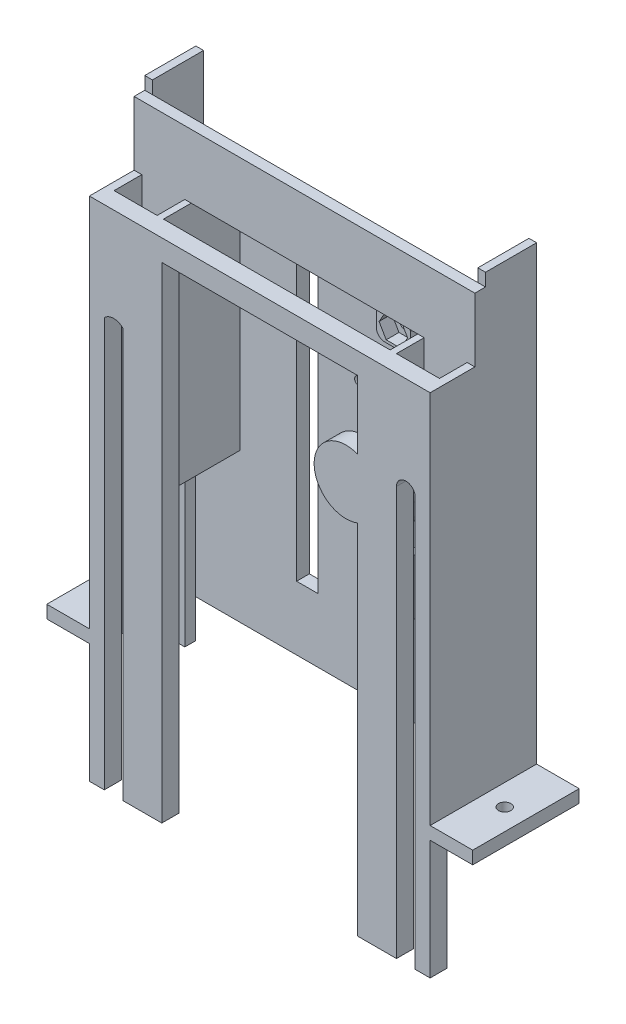
SolidWorks part; units mm, degrees
ref_plane "Front Plane" through (0, 0, 0) normal (0, 0, 1) x (1, 0, 0)
ref_plane "Top Plane" through (0, 0, 0) normal (0, 1, 0) x (1, 0, 0)
ref_plane "Right Plane" through (0, 0, 0) normal (1, 0, 0) x (0, 0, -1)
sketch "Sketch1" plane through (0, 0, 0) normal (0, 0, 1) x (1, 0, 0)
  line L0 (0, 87.3129) -> (0, -99.6485)
  line L1 (-40, 28) -> (40, 28)
  line L2 (-40, 28) -> (-40, -28)
  line L3 (-40, -28) -> (40, -28)
  line L4 (40, 28) -> (40, -28)
  line L5 (-40, 28) -> (40, -28) construction
  line L6 (-40, -28) -> (40, 28) construction
  line L7 (-23, 58.4535) -> (-23, -153.9501)
  line L8 (-36.5, -28) -> (-36.5, 23)
  line L13 (-36.5, 23) -> (-32.1, 23)
  line L14 (-32.1, 23) -> (-32.1, -28)
  line L15 (23, 58.4535) -> (23, -153.9501)
  line L16 (32.1, 23) -> (32.1, -28)
  line L17 (36.5, 23) -> (32.1, 23)
  line L18 (36.5, -28) -> (36.5, 23)
  line L19 (40, 28) -> (40, -28)
  line L20 (-34.3, 23) -> (34.3, 23)
  arc A0 (-36.5, 23) -> (-32.1, 23) centre (-34.3, 23) cw
  arc A1 (36.5, 23) -> (32.1, 23) centre (34.3, 23) ccw
  point P0 (0, 0)
  dimension "D1" = 17
  dimension "D2" = 80
  dimension "D3" = 56
  dimension "D4" = 4.4
  dimension "D5" = 5
  dimension "D6" = 3.5
extrude "Boss-Extrude1" add sketch "Sketch1" along normal blind 4 contours L8 A0 L20 L7 L1 L2 L3 | L20 L14 L3 L7 | L7 L20 L0 L1 | L20 L15 L3 L16 | L0 L20 L15 L1 | A1 L18 L3 L4 L1 L15 L20
sketch "Sketch2" plane through (0, 0, 0) normal (0, 0, -1) x (-1, 0, 0)
  line L0 (-38.2, 28) -> (-38.2, -28)
  line L1 (-28.1, 28) -> (-28.1, -28)
  line L2 (-26.6, 28) -> (-26.6, -28)
  line L3 (0, 45.2622) -> (0, -39.8517) construction
  line L4 (36.5, -28) -> (36.5, 23)
  line L5 (40, -28) -> (36.5, -28)
  line L6 (40, 28) -> (40, -28)
  line L7 (23, -28) -> (23, 23)
  line L8 (32.1, -28) -> (23, -28)
  line L9 (32.1, 23) -> (32.1, -28)
  line L10 (26.6, 28) -> (26.6, -28)
  line L11 (28.1, 28) -> (28.1, -28)
  line L12 (38.2, 28) -> (38.2, -28)
  line L14 (-32.1, 23) -> (-32.1, -28)
  line L15 (-32.1, -28) -> (-23, -28)
  line L16 (-23, -28) -> (-23, 23)
  line L17 (-23, 23) -> (23, 23)
  line L18 (23, 23) -> (23, -28)
  line L19 (23, -28) -> (32.1, -28)
  line L20 (32.1, -28) -> (32.1, 23)
  line L21 (36.5, 23) -> (36.5, -28)
  line L22 (36.5, -28) -> (40, -28)
  line L23 (40, -28) -> (40, 28)
  line L24 (40, 28) -> (-40, 28)
  line L25 (-40, 28) -> (-40, -28)
  line L26 (-40, -28) -> (-36.5, -28)
  line L27 (-36.5, -28) -> (-36.5, 23)
  line L28 (-32.1, 23) -> (-32.1, -28)
  line L29 (-32.1, -28) -> (-23, -28)
  line L30 (-23, -28) -> (-23, 23)
  line L31 (-23, 23) -> (23, 23)
  line L32 (23, 23) -> (23, -28)
  line L33 (23, -28) -> (32.1, -28)
  line L34 (32.1, -28) -> (32.1, 23)
  line L35 (36.5, 23) -> (36.5, -28)
  line L36 (36.5, -28) -> (40, -28)
  line L37 (40, -28) -> (40, 28)
  line L38 (40, 28) -> (-40, 28)
  line L39 (-40, 28) -> (-40, -28)
  line L40 (-40, -28) -> (-36.5, -28)
  line L41 (-36.5, -28) -> (-36.5, 23)
  arc A0 (32.1, 23) -> (36.5, 23) centre (34.3, 23) cw
  arc A2 (36.5, 23) -> (32.1, 23) centre (34.3, 23) ccw
  arc A3 (-32.1, 23) -> (-36.5, 23) centre (-34.3, 23) ccw
  arc A4 (36.5, 23) -> (32.1, 23) centre (34.3, 23) ccw
  arc A5 (-32.1, 23) -> (-36.5, 23) centre (-34.3, 23) ccw
  line M22 (-32.1, -28) -> (-23, -28)
  line M31 (40, -28) -> (40, 28)
  line M32 (40, 28) -> (-40, 28)
  line M33 (-40, 28) -> (-40, -28)
  line M34 (-40, -28) -> (-36.5, -28)
  dimension "D2" = 1.8
  dimension "D3" = 1.5
  dimension "D4" = 10.1
  dimension "D1" = 0
extrude "Boss-Extrude2" add sketch "Sketch2" along normal blind 5 contours L0 M32 M33 M34 | L2 L1 M32 M22 | L11 L10 L8 M32 | L12 L5 M32 M31
sketch "Sketch3" plane through (0, 0, -5) normal (0, 0, -1) x (-1, 0, 0)
  line L0 (-28.1, 28) -> (-28.1, -28) construction
  line L1 (-28.1, 15) -> (-26.6, 15)
  line L2 (-28.1, 15) -> (-28.1, -15)
  line L3 (-28.1, -15) -> (-26.6, -15)
  line L4 (-26.6, 15) -> (-26.6, -15)
  line L5 (-26.6, 28) -> (-26.6, -28) construction
  point P8 (-26.6, 0)
  dimension "D1" = 30
extrude "Cut-Extrude1" cut sketch "Sketch3" against normal up to surface (5 mm away) up to face at (0, -1.25, 0)
sketch "Sketch4" plane through (0, 28, 0) normal (0, 1, 0) x (1, 0, 0)
  line L0 (-40, 5) -> (-40, 21)
  line L1 (-40, 21) -> (40, 21)
  line L2 (40, 21) -> (40, 5)
  line L3 (38.2, 5) -> (38.2, 21)
  line L4 (28.1, 5) -> (28.1, 21)
  line L5 (26.6, 5) -> (26.6, 21)
  line L6 (-26.6, 5) -> (-26.6, 21)
  line L7 (-28.1, 5) -> (-28.1, 21)
  line L8 (-38.2, 5) -> (-38.2, 21)
  line L9 (-40, 18) -> (40, 18)
  line L10 (-40, 5) -> (-38.2, 5) construction
  line M5 (-38.2, 5) -> (-40, 5)
  line M9 (40, 5) -> (38.2, 5)
  line M13 (28.1, 5) -> (26.6, 5)
  line M17 (-26.6, 5) -> (-28.1, 5)
  dimension "D1" = 3
  dimension "D2" = 16
extrude "Boss-Extrude3" add sketch "Sketch4" against normal up to surface (56 mm away) contours L9 L0 L8 M5 | L9 L7 L6 M17 | L7 L9 L6 L1 | L8 L9 L7 L1 | L0 L9 L8 L1 | L6 L9 L5 L1 | L9 L5 L4 M13 | L5 L9 L4 L1 | L4 L9 L3 L1 | L3 L9 L2 L1 | L9 L3 L2 M9 up to face at (-27.45, -28, -0.25)
sketch "Sketch5" plane through (0, 0, -21) normal (0, 0, -1) x (-1, 0, 0)
  line L0 (-40, -28) -> (-40, 28) construction
  circle A0 centre (-12.36, 17.5) radius 1.75
  circle A1 centre (-12.36, -17.5) radius 1.75
  circle A2 centre (-20.26, 0) radius 4.75
  dimension "D1" = 3.5
  dimension "D2" = 3.5
  dimension "D3" = 9.5
  dimension "D4" = 19.74
  dimension "D5" = 27.64
  dimension "D6" = 17.5
  dimension "D7" = 17.5
extrude "Cut-Extrude2" cut sketch "Sketch5" against normal up to surface (3 mm away) up to face at (0, 0, -18)
sketch "Sketch6" plane through (0, 0, -18) normal (0, 0, 1) x (1, 0, 0)
  line L1 (14.0343, 14.6) -> (15.7086, 17.5)
  line L2 (15.7086, 17.5) -> (14.0343, 20.4)
  line L3 (14.0343, 20.4) -> (10.6857, 20.4)
  line L4 (10.6857, 20.4) -> (9.0114, 17.5)
  line L5 (9.0114, 17.5) -> (10.6857, 14.6)
  line L6 (10.6857, 14.6) -> (14.0343, 14.6)
  line L7 (14.0343, -20.4) -> (15.7086, -17.5)
  line L8 (15.7086, -17.5) -> (14.0343, -14.6)
  line L9 (14.0343, -14.6) -> (10.6857, -14.6)
  line L10 (10.6857, -14.6) -> (9.0114, -17.5)
  line L11 (9.0114, -17.5) -> (10.6857, -20.4)
  line L12 (10.6857, -20.4) -> (14.0343, -20.4)
  line L13 (8.36, 21) -> (16.36, 21)
  line L14 (8.36, 21) -> (8.36, 14)
  line L15 (8.36, 14) -> (16.36, 14)
  line L16 (16.36, 21) -> (16.36, 14)
  line L17 (8.36, 21) -> (16.36, 14) construction
  line L18 (8.36, 14) -> (16.36, 21) construction
  line L19 (8.36, -14) -> (16.36, -14)
  line L20 (8.36, -14) -> (8.36, -21)
  line L21 (8.36, -21) -> (16.36, -21)
  line L22 (16.36, -14) -> (16.36, -21)
  line L23 (8.36, -14) -> (16.36, -21) construction
  line L24 (8.36, -21) -> (16.36, -14) construction
  circle A0 centre (12.36, 17.5) radius 1.75 construction
  circle A1 centre (12.36, 17.5) radius 1.75
  circle A2 centre (12.36, -17.5) radius 1.75 construction
  circle A3 centre (12.36, -17.5) radius 1.75
  circle A4 centre (12.36, 17.5) radius 2.9 construction
  circle A5 centre (12.36, -17.5) radius 2.9 construction
  dimension "D1" = 5.8
  dimension "D2" = 7
  dimension "D3" = 8
  dimension "D4" = 5.8
  dimension "D5" = 8
  dimension "D6" = 7
extrude "Boss-Extrude4" add sketch "Sketch6" along normal blind 3 contours L16 L13 L14 L15 L6 L5 L4 L3 L2 L1 | L22 L19 L20 L21 L12 L11 L10 L9 L8 L7
fillet "Fillet1" radius 2 8 edges at (16.36, 14, -16.5) (8.36, 14, -16.5) (16.36, 21, -16.5) (8.36, 21, -16.5) (16.36, -14, -16.5) (8.36, -14, -16.5) (16.36, -21, -16.5) (8.36, -21, -16.5)
sketch "Sketch7" plane through (0, 0, -5) normal (0, 0, 1) x (1, 0, 0)
  line L4 (28.1, 15) -> (26.6, 15)
  line L5 (26.6, 15) -> (26.6, -15)
  line L6 (26.6, -15) -> (28.1, -15)
  line L7 (28.1, -15) -> (28.1, 15)
  line L8 (28.1, 15) -> (26.6, 15)
  line L9 (26.6, 15) -> (26.6, -15)
  line L10 (26.6, -15) -> (28.1, -15)
  line L11 (28.1, -15) -> (28.1, 15)
  dimension "D1" = 0
extrude "Cut-Extrude3" cut sketch "Sketch7" against normal blind 7
sketch "Sketch8" plane through (0, 0, -21) normal (0, 0, -1) x (-1, 0, 0)
  line L0 (-40, -28) -> (40, -28) construction
  line L1 (13.35, -28) -> (8.35, -28)
  line L2 (13.35, -28) -> (13.35, 22)
  line L3 (13.35, 22) -> (8.35, 22)
  line L4 (8.35, -28) -> (8.35, 22)
  line L5 (40, -28) -> (40, 28) construction
  arc A0 (8.35, 22) -> (13.35, 22) centre (10.85, 22) cw
  line M7 (-40, -28) -> (40, -28)
  dimension "D1" = 5
  dimension "D2" = 50
  dimension "D3" = 26.65
extrude "Cut-Extrude4" cut sketch "Sketch8" against normal up to surface (3 mm away) contours L4 L2 L3 M7 | A0 L3 up to face at (12.36, -17.5, -18)
sketch "Sketch11" plane through (0, 0, -21) normal (0, 0, -1) x (-1, 0, 0)
  line L0 (-40, -28) -> (8.35, -28) construction
  line L1 (-24, -28) -> (-17, -28)
  line L2 (-24, -28) -> (-24, -25)
  line L3 (-24, -25) -> (-17, -25)
  line L4 (-17, -28) -> (-17, -25)
  line L5 (13.35, -28) -> (40, -28) construction
  line L6 (24, -28) -> (17, -28)
  line L7 (24, -28) -> (24, -25)
  line L8 (24, -25) -> (17, -25)
  line L9 (17, -28) -> (17, -25)
  line L10 (-40, -28) -> (-40, 28) construction
  line L11 (40, -28) -> (40, 28) construction
  dimension "D1" = 7
  dimension "D2" = 7
  dimension "D3" = 3
  dimension "D4" = 3
  dimension "D5" = 16
  dimension "D6" = 16
extrude "Boss-Extrude5" add sketch "Sketch11" along normal blind 10
sketch "Sketch12" plane through (40, 0, 0) normal (1, 0, 0) x (0, 0, -1)
  line L1 (-4, -28) -> (21, -28)
  line L2 (-4, -28) -> (-4, -25)
  line L3 (-4, -25) -> (21, -25)
  line L4 (21, -28) -> (21, -25)
extrude "Boss-Extrude6" add sketch "Sketch12" along normal blind 10
sketch "Sketch13" plane through (-40, 0, 0) normal (-1, 0, 0) x (0, 0, 1)
  line L4 (-21, -28) -> (4, -28)
  line L5 (-21, -25) -> (-21, -28)
  line L6 (4, -25) -> (-21, -25)
  line L7 (4, -28) -> (4, -25)
  line L8 (-21, -28) -> (4, -28)
  line L9 (-21, -25) -> (-21, -28)
  line L10 (4, -25) -> (-21, -25)
  line L11 (4, -28) -> (4, -25)
  dimension "D1" = 0
extrude "Boss-Extrude7" add sketch "Sketch13" along normal blind 10
sketch "Sketch14" plane through (0, -25, 0) normal (0, 1, 0) x (1, 0, 0)
  line L0 (40, 21) -> (40, -4) construction
  line L1 (40, -4) -> (50, -4) construction
  line L2 (50, -4) -> (50, 21) construction
  line L3 (50, 21) -> (40, 21) construction
  line L4 (17, 21) -> (24, 21) construction
  line L5 (24, 21) -> (24, 31) construction
  line L6 (24, 31) -> (17, 31) construction
  line L7 (17, 31) -> (17, 21) construction
  line L8 (-40, -4) -> (-40, 21) construction
  line L9 (-40, 21) -> (-50, 21) construction
  line L10 (-50, 21) -> (-50, -4) construction
  line L11 (-50, -4) -> (-40, -4) construction
  line L12 (-24, 21) -> (-17, 21) construction
  line L13 (-17, 21) -> (-17, 31) construction
  line L14 (-17, 31) -> (-24, 31) construction
  line L15 (-24, 31) -> (-24, 21) construction
  line L16 (40, 21) -> (40, -4)
  line L17 (40, -4) -> (50, -4)
  line L18 (50, -4) -> (50, 21)
  line L19 (50, 21) -> (40, 21)
  line L20 (17, 21) -> (24, 21)
  line L21 (24, 21) -> (24, 31)
  line L22 (24, 31) -> (17, 31)
  line L23 (17, 31) -> (17, 21)
  line L24 (-40, -4) -> (-40, 21)
  line L25 (-40, 21) -> (-50, 21)
  line L26 (-50, 21) -> (-50, -4)
  line L27 (-50, -4) -> (-40, -4)
  line L28 (-24, 21) -> (-17, 21)
  line L29 (-17, 21) -> (-17, 31)
  line L30 (-17, 31) -> (-24, 31)
  line L31 (-24, 31) -> (-24, 21)
  circle A0 centre (-45, 8.5) radius 1.75
  circle A1 centre (-20.5, 26) radius 1.75
  circle A2 centre (20.5, 26) radius 1.75
  circle A3 centre (45, 8.5) radius 1.75
  point P20 (-40, 8.5)
  point P28 (-45, 21)
  point P31 (45, 21)
  point P33 (-17, 26)
  point P36 (-20.5, 31)
  point P38 (20.5, 31)
  dimension "D1" = 3.5
extrude "Cut-Extrude6" cut sketch "Sketch14" against normal blind 3 contours A2 | A3 | A1 | A0
sketch "Sketch15" plane through (0, 0, 4) normal (0, 0, 1) x (1, 0, 0)
  circle A0 centre (20.26, 0) radius 4.75 construction
  circle A1 centre (20.26, 0) radius 4.75
  circle A2 centre (20.26, 0) radius 7.5
  line M19 (23, 23) -> (23, -28)
  dimension "D1" = 15
extrude "Boss-Extrude8" add sketch "Sketch15" against normal blind 4 contours A2 A1 M19 | A1 M19 | A2 A1 M19 | A1 M19
sketch "Sketch17" plane through (0, 0, -21) normal (0, 0, -1) x (-1, 0, 0)
  line L0 (34.3, 23) -> (-34.3, 23) construction
  line L1 (-23, 58.4535) -> (-23, -153.9501) construction
  line L2 (32.1, 23) -> (32.1, -28) construction
  line L3 (36.5, 23) -> (32.1, 23) construction
  line L4 (36.5, -28) -> (36.5, 23) construction
  line L5 (23, 58.4535) -> (23, -153.9501) construction
  line L6 (40, 28) -> (-40, 28) construction
  line L7 (40, 28) -> (40, -28) construction
  line L8 (40, -28) -> (-40, -28) construction
  line L9 (-40, 28) -> (-40, -28) construction
  line L10 (-40, 28) -> (-40, -28) construction
  line L11 (0, 87.3129) -> (0, -99.6485) construction
  line L12 (-36.5, -28) -> (-36.5, 23) construction
  line L13 (-36.5, 23) -> (-32.1, 23) construction
  line L14 (-32.1, 23) -> (-32.1, -28) construction
  line L15 (34.3, 23) -> (-34.3, 23)
  line L16 (-23, 58.4535) -> (-23, -153.9501)
  line L17 (32.1, 23) -> (32.1, -28)
  line L18 (36.5, 23) -> (32.1, 23)
  line L19 (36.5, -28) -> (36.5, 23)
  line L20 (23, 58.4535) -> (23, -153.9501)
  line L21 (40, 28) -> (-40, 28)
  line L22 (40, 28) -> (40, -28)
  line L23 (40, -28) -> (-40, -28)
  line L24 (-40, 28) -> (-40, -28)
  line L25 (-40, 28) -> (-40, -28)
  line L26 (0, 87.3129) -> (0, -99.6485)
  line L27 (-36.5, -28) -> (-36.5, 23)
  line L28 (-36.5, 23) -> (-32.1, 23)
  line L29 (-32.1, 23) -> (-32.1, -28)
  line L30 (-36, -28) -> (-36, 23)
  line L31 (-32.6, 23) -> (-32.6, -28)
  line L32 (32.6, 23) -> (32.6, -28)
  line L33 (36, -28) -> (36, 23)
  line L34 (-36.5, -9.1991) -> (-32.1, -9.1991)
  line L35 (-32.1, -9.1991) -> (36.5, -9.1991)
  arc A0 (36.5, 23) -> (32.1, 23) centre (34.3, 23) ccw construction
  arc A1 (-32.1, 23) -> (-36.5, 23) centre (-34.3, 23) ccw construction
  arc A2 (36.5, 23) -> (32.1, 23) centre (34.3, 23) ccw
  arc A3 (-32.1, 23) -> (-36.5, 23) centre (-34.3, 23) ccw
  arc A4 (-32.6, 23) -> (-36, 23) centre (-34.3, 23) ccw
  arc A5 (36, 23) -> (32.6, 23) centre (34.3, 23) ccw
  line M13 (-50, -28) -> (-24, -28)
  dimension "D1" = 0.5
  dimension "D2" = 0.5
  dimension "D3" = 0.5
  dimension "D4" = 0.5
  dimension "D5" = 0.5
  dimension "D6" = 0.5
extrude "Cut-Extrude8" cut sketch "Sketch17" against normal blind 4 contours L31 L28 L30 M13 | L23 L33 L18 L15 L32
sketch "Sketch18" plane through (0, 0, -21) normal (0, 0, -1) x (-1, 0, 0)
  line L1 (-26.26, 6) -> (-3.26, 6)
  line L2 (-26.26, 6) -> (-26.26, -6)
  line L3 (-26.26, -6) -> (-3.26, -6)
  line L4 (-3.26, 6) -> (-3.26, -6)
  circle A0 centre (-20.26, 0) radius 4.75 construction
  dimension "D4" = 6
  dimension "D1" = 12
  dimension "D2" = 23
  dimension "D3" = 6
extrude "Cut-Extrude9" cut sketch "Sketch18" against normal blind 10
sketch "Sketch19" plane through (0, -28, 0) normal (0, -1, 0) x (1, 0, 0)
  line L0 (-24, -21) -> (-50, -21) construction
  line L1 (-50, 4) -> (-38.2, 4)
  line L2 (-50, 4) -> (-50, -21)
  line L3 (-50, -21) -> (-38.2, -21)
  line L4 (-38.2, 0) -> (-38.2, -18)
  line L5 (36.5, 4) -> (50, 4) construction
  line L6 (38.2, 4) -> (50, 4)
  line L7 (38.2, 0) -> (38.2, -18)
  line L8 (38.2, -21) -> (50, -21)
  line L9 (50, 4) -> (50, -21)
  line L10 (-24, -21) -> (-38.2, -21)
  line L11 (38.2, 4) -> (-38.2, 4)
  line L13 (38.2, 0) -> (-38.2, 0)
  line L15 (38.2, -21) -> (24, -21)
  line L17 (38.2, -18) -> (-38.2, -18)
  line L20 (17, -21) -> (17, -31)
  line L21 (17, -31) -> (24, -31)
  line L22 (24, -21) -> (24, -31)
  line L24 (-24, -21) -> (-24, -31)
  line L25 (-24, -31) -> (-17, -31)
  line L26 (-17, -21) -> (-17, -31)
  line L27 (17, -21) -> (-17, -21)
  dimension "D1" = 11.8
  dimension "D2" = 11.8
  dimension "D3" = 4
  dimension "D4" = 3
  dimension "D5" = 11.8
  dimension "D6" = 11.8
extrude "Boss-Extrude10" add sketch "Sketch19" along normal blind 35
sketch "Sketch21" plane through (0, -63, 0) normal (0, -1, 0) x (1, 0, 0)
  circle A0 centre (45, -8.5) radius 1.45
  circle A1 centre (20.5, -26) radius 1.45
  circle A2 centre (-20.5, -26) radius 1.45
  circle A3 centre (-45, -8.5) radius 1.45
  dimension "D1" = 2.9
  dimension "D2" = 2.9
  dimension "D3" = 2.9
  dimension "D4" = 2.9
extrude "Cut-Extrude11" cut sketch "Sketch21" against normal through all
sketch "Sketch20" plane through (0, -25, 0) normal (0, 1, 0) x (1, 0, 0)
  line L1 (-50, 21) -> (-40, 21)
  line L2 (-50, 21) -> (-50, -4)
  line L3 (-50, -4) -> (-40, -4)
  line L4 (-40, 21) -> (-40, -4)
  line L5 (40, 21) -> (50, 21)
  line L6 (40, 21) -> (40, -4)
  line L7 (40, -4) -> (50, -4)
  line L8 (50, 21) -> (50, -4)
  line L9 (-24, 31) -> (-17, 31)
  line L10 (-24, 31) -> (-24, 21)
  line L11 (-24, 21) -> (-17, 21)
  line L12 (-17, 31) -> (-17, 21)
  line L13 (17, 31) -> (24, 31)
  line L14 (17, 31) -> (17, 21)
  line L15 (17, 21) -> (24, 21)
  line L16 (24, 31) -> (24, 21)
extrude "Cut-Extrude10" cut sketch "Sketch20" against normal blind 35
sketch "Sketch22" plane through (0, 0, 4) normal (0, 0, 1) x (1, 0, 0)
  line L0 (50, -63) -> (-50, -63) construction
  line L1 (-36.5, -28) -> (-32.1, -28)
  line L2 (-36.5, -28) -> (-36.5, -63)
  line L3 (-36.5, -63) -> (-32.1, -63)
  line L4 (-32.1, -28) -> (-32.1, -63)
  line L6 (32.1, -28) -> (36.5, -28)
  line L7 (32.1, -28) -> (32.1, -63)
  line L8 (32.1, -63) -> (36.5, -63)
  line L9 (36.5, -28) -> (36.5, -63)
extrude "Cut-Extrude12" cut sketch "Sketch22" against normal blind 10
sketch "Sketch23" plane through (0, 0, 4) normal (0, 0, 1) x (1, 0, 0)
  line L0 (32.1, -63) -> (-32.1, -63) construction
  line L1 (-23, -28) -> (23, -28)
  line L2 (-23, -28) -> (-23, -63)
  line L3 (-23, -63) -> (23, -63)
  line L4 (23, -28) -> (23, -63)
  line L5 (23, -6.9816) -> (23, -28) construction
  dimension "D1" = 0
extrude "Cut-Extrude13" cut sketch "Sketch23" against normal blind 10
sketch "Sketch25" plane through (0, 28, 0) normal (0, 1, 0) x (1, 0, 0)
  line L0 (38.2, 18) -> (38.2, 0) construction
  line L1 (40, 21) -> (38.2, 21)
  line L2 (40, 21) -> (40, 9)
  line L3 (40, 9) -> (38.2, 9)
  line L4 (38.2, 21) -> (38.2, 9)
  line L5 (-38.2, 18) -> (-38.2, 0) construction
  line L6 (-40, 21) -> (-38.2, 21)
  line L7 (-40, 21) -> (-40, 9)
  line L8 (-40, 9) -> (-38.2, 9)
  line L9 (-38.2, 21) -> (-38.2, 9)
  dimension "D1" = 12
  dimension "D2" = 12
extrude "Boss-Extrude12" add sketch "Sketch25" along normal blind 18
sketch "Sketch27" plane through (0, 0, -21) normal (0, 0, -1) x (-1, 0, 0)
  circle A0 centre (-1.26, 0) radius 1
  circle A1 centre (-28.56, 0) radius 1
extrude "Cut-Extrude15" cut sketch "Sketch27" against normal blind 5
sketch "Sketch28" plane through (0, -60, 0) normal (0, 1, 0) x (1, 0, 0)
  line L0 (-38.2, 21) -> (38.2, 21) construction
  line L1 (17, 31) -> (24, 31)
  line L2 (17, 31) -> (17, 21)
  line L3 (17, 21) -> (24, 21)
  line L4 (24, 31) -> (24, 21)
  line L5 (24, 21) -> (24, 31) construction
  line L18 (-24, 31) -> (-17, 31)
  line L19 (-24, 31) -> (-24, 21)
  line L20 (-24, 21) -> (-17, 21)
  line L21 (-17, 31) -> (-17, 21)
  line L26 (-24, 31) -> (-24, 21) construction
  line L27 (-17, 31) -> (-24, 31) construction
  dimension "D3" = 10
  dimension "D4" = 7
extrude "Cut-Extrude16" cut sketch "Sketch28" against normal through all contours L2 L1 L4 L3 | L18 L21 L20 L19
sketch "Sketch29" plane through (0, -63, 0) normal (0, 1, 0) x (1, 0, 0)
  line L0 (9.6, 31) -> (16.6, 31)
  line L1 (9.6, 31) -> (9.6, 21)
  line L2 (9.6, 21) -> (16.6, 21)
  line L3 (16.6, 31) -> (16.6, 21)
  line L4 (-16.6, 31) -> (-9.6, 31)
  line L5 (-16.6, 31) -> (-16.6, 21)
  line L6 (-16.6, 21) -> (-9.6, 21)
  line L7 (-9.6, 31) -> (-9.6, 21)
  line L8 (-38.2, 21) -> (38.2, 21) construction
  line L9 (-26.6, 18) -> (-26.6, 0) construction
  line L10 (26.6, 18) -> (26.6, 0) construction
  dimension "D1" = 10
  dimension "D2" = 10
  dimension "D3" = 7
  dimension "D4" = 7
  dimension "D5" = 0
  dimension "D6" = 0
  dimension "D7" = 10
  dimension "D8" = 10
extrude "Boss-Extrude13" add sketch "Sketch29" along normal blind 2
sketch "Sketch30" plane through (0, 28, 0) normal (0, 1, 0) x (1, 0, 0)
  line L0 (16.6, 31) -> (9.6, 31) construction
  line L1 (-9.6, 31) -> (-16.6, 31) construction
  line L2 (16.6, 21) -> (16.6, 31) construction
  line L3 (-9.6, 21) -> (-9.6, 31) construction
  circle A0 centre (13.1, 26.5) radius 1.5
  circle A1 centre (-13.1, 26.5) radius 1.5
  dimension "D1" = 3
  dimension "D2" = 3
  dimension "D5" = 3.5
  dimension "D6" = 3.5
  dimension "D3" = 4.5
  dimension "D4" = 4.5
extrude "Cut-Extrude17" cut sketch "Sketch30" against normal through all
sketch "Sketch31" plane through (0, 0, 4) normal (0, 0, 1) x (1, 0, 0)
sketch "Sketch32" plane through (0, 0, 4) normal (0, 0, 1) x (1, 0, 0)
  line L0 (-38, 26) -> (-30, 26)
  line L1 (-38, 26) -> (-38, 5)
  line L2 (-38, 5) -> (-36.5, 5)
  line L3 (-30, 26) -> (-30, 5)
  line L4 (-32.1, 5) -> (-30, 5)
  line L5 (-40, 28) -> (40, 28) construction
  line L6 (-40, 28) -> (-40, -60) construction
  line L7 (-36.5, -63) -> (-36.5, 23) construction
  line L8 (-32.1, 23) -> (-32.1, -63) construction
  arc A0 (-36.5, 5) -> (-32.1, 5) centre (-34.3, 2.9604) cw
  dimension "D3" = 3
  dimension "D1" = 21
  dimension "D2" = 8
  dimension "D4" = 2
  dimension "D5" = 2
extrude "Boss-Extrude14" add sketch "Sketch32" against normal up to surface (4 mm away) up to face at (27.35, -21.5, 0)
sketch "Sketch33" plane through (0, -63, 0) normal (0, -1, 0) x (1, 0, 0)
  line L1 (40, 0) -> (36.5, 0)
  line L2 (40, 0) -> (40, 4)
  line L3 (40, 4) -> (36.5, 4)
  line L4 (36.5, 0) -> (36.5, 4)
  line L5 (-40, 0) -> (-36.5, 0)
  line L6 (-40, 0) -> (-40, 4)
  line L7 (-40, 4) -> (-36.5, 4)
  line L8 (-36.5, 0) -> (-36.5, 4)
  line L9 (-32.1, 4) -> (-23, 4)
  line L10 (-32.1, 4) -> (-32.1, 0)
  line L11 (-32.1, 0) -> (-23, 0)
  line L12 (-23, 4) -> (-23, 0)
  line L13 (23, 4) -> (32.1, 4)
  line L14 (23, 4) -> (23, 0)
  line L15 (23, 0) -> (32.1, 0)
  line L16 (32.1, 4) -> (32.1, 0)
  dimension "D1" = 4
  dimension "D2" = 3.5
  dimension "D3" = 4
  dimension "D4" = 3.5
extrude "Boss-Extrude15" add sketch "Sketch33" along normal blind 28
sketch "Sketch34" plane through (0, 0, 4) normal (0, 0, 1) x (1, 0, 0)
  line L0 (40, 28) -> (40, -60) construction
  line L1 (30, 26) -> (38, 26)
  line L2 (30, 26) -> (30, 5)
  line L3 (30, 5) -> (32.1, 5)
  line L4 (38, 26) -> (38, 5)
  line L5 (-40, 28) -> (40, 28) construction
  line L6 (32.1, 23) -> (32.1, -91) construction
  line L7 (36.5, 5) -> (38, 5)
  arc A0 (32.1, 5) -> (36.5, 5) centre (34.3, 5) cw
  dimension "D6" = 2.2
  dimension "D1" = 8
  dimension "D2" = 2
  dimension "D3" = 2
  dimension "D4" = 21
  dimension "D5" = 2.2
extrude "Boss-Extrude16" add sketch "Sketch34" against normal up to surface (4 mm away) up to face at (27.35, -21.5, 0)
sketch "Sketch35" plane through (0, 0, -9) normal (0, 0, 1) x (1, 0, 0)
  line L1 (-40, 43) -> (40, 43)
  line L2 (-40, 43) -> (-40, 28)
  line L3 (-40, 28) -> (40, 28)
  line L4 (40, 43) -> (40, 28)
  dimension "D1" = 15
  dimension "D2" = 80
extrude "Boss-Extrude17" add sketch "Sketch35" along normal blind 2.5
sketch "Sketch36" plane through (0, 28, 0) normal (0, -1, 0) x (1, 0, 0)
  line L0 (-28.1, -18) -> (-28.1, 0) construction
  line L1 (-38.2, -6.5) -> (-28.1, -6.5)
  line L2 (-38.2, -6.5) -> (-38.2, -9)
  line L3 (-38.2, -9) -> (-28.1, -9)
  line L4 (-28.1, -6.5) -> (-28.1, -9)
  line L6 (28.1, -6.5) -> (38.2, -6.5)
  line L7 (28.1, -6.5) -> (28.1, -9)
  line L8 (28.1, -9) -> (38.2, -9)
  line L9 (38.2, -6.5) -> (38.2, -9)
extrude "Boss-Extrude18" add sketch "Sketch36" along normal up to surface (91 mm away) up to face at (11.6, -63, -26.5)
sketch "Sketch37" plane through (0, 0, -21) normal (0, 0, -1) x (-1, 0, 0)
  line L9 (13.35, -28) -> (8.35, -28)
  line L10 (13.35, -28) -> (13.35, -48)
  line L11 (13.35, -48) -> (8.35, -48)
  line L12 (8.35, -28) -> (8.35, -48)
  dimension "D1" = 5
  dimension "D2" = 20
extrude "Cut-Extrude18" cut sketch "Sketch37" against normal blind 5
